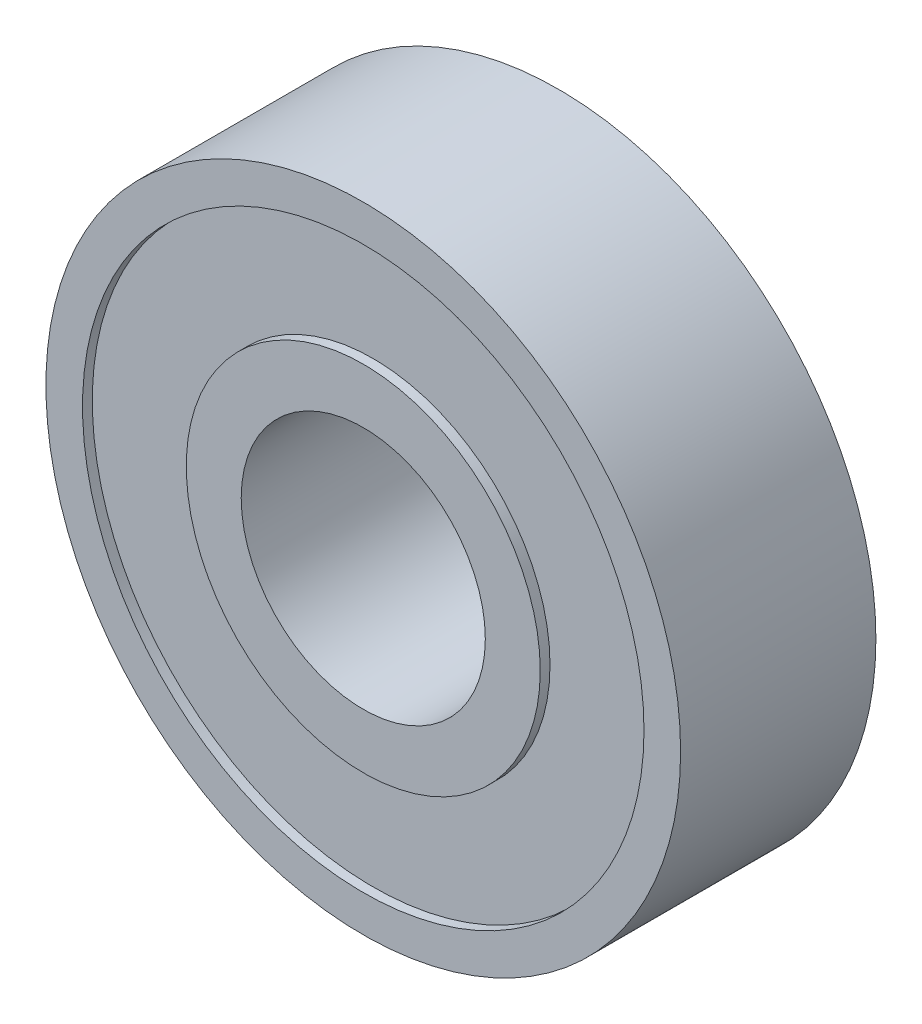
SolidWorks part; units mm, degrees
material "Chrome Stainless Steel"
ref_plane "Front" through (0, 0, 0) normal (0, 0, 1) x (1, 0, 0)
ref_plane "Top" through (0, 0, 0) normal (0, 1, 0) x (1, 0, 0)
ref_plane "Right" through (0, 0, 0) normal (1, 0, 0) x (0, 0, -1)
sketch "Sketch1" plane through (0, 0, 0) normal (0, 0, 1) x (1, 0, 0)
  circle A0 centre (0, 0) radius 13
  circle A1 centre (0, 0) radius 5
  dimension "D1" = 26
  dimension "D2" = 10
extrude "Extrude1" add sketch "Sketch1" along normal mid plane 8
sketch "Sketch2" plane through (0, 0, 4) normal (0, 0, 1) x (1, 0, 0)
  circle A2 centre (0, 0) radius 7.25
  circle A3 centre (0, 0) radius 7.25
  circle A5 centre (0, 0) radius 11.5
  circle A6 centre (0, 0) radius 11.5
  dimension "D1" = 2.25
  dimension "D2" = 1.5
extrude "Cut-Extrude1" cut sketch "Sketch2" against normal blind 0.4
mirror "Mirror1" about plane through (0, 0, 0) normal (0, 0, 1) of "Cut-Extrude1"
